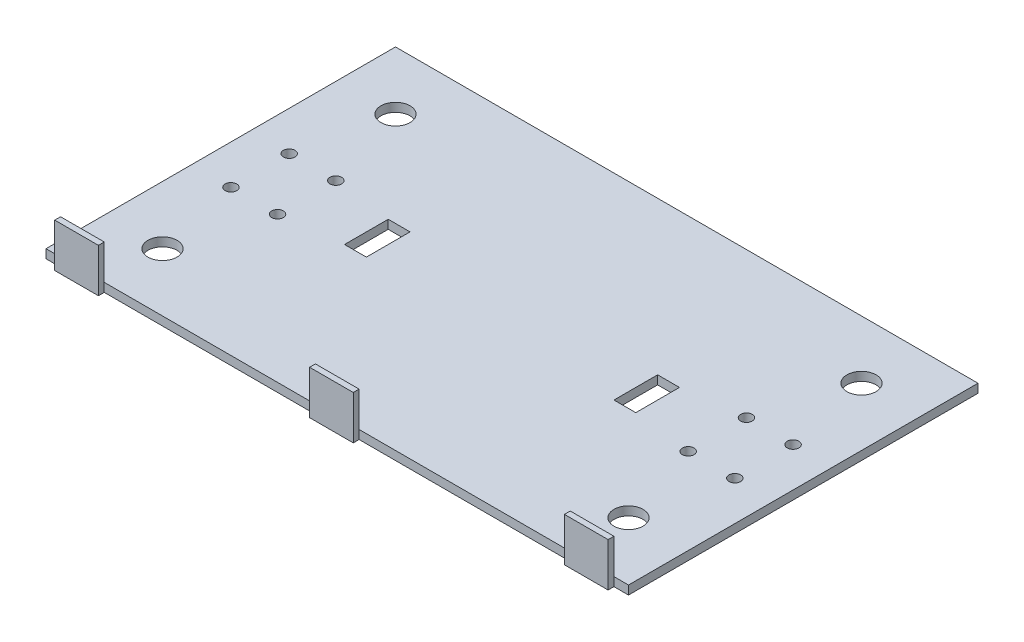
SolidWorks part; units mm, degrees
ref_plane "Front Plane" through (0, 0, 0) normal (0, 0, 1) x (1, 0, 0)
ref_plane "Top Plane" through (0, 0, 0) normal (0, 1, 0) x (1, 0, 0)
ref_plane "Right Plane" through (0, 0, 0) normal (1, 0, 0) x (0, 0, -1)
sketch "Sketch1" plane through (0, 0, 0) normal (0, 1, 0) x (1, 0, 0)
  line L1 (100, -60) -> (-100, -60)
  line L2 (100, -60) -> (100, 60)
  line L3 (100, 60) -> (-100, 60)
  line L4 (-100, -60) -> (-100, 60)
  line L5 (100, -60) -> (-100, 60) construction
  line L6 (100, 60) -> (-100, -60) construction
  point P0 (0, 0)
  dimension "D1" = 200
  dimension "D2" = 120
extrude "Boss-Extrude3" add sketch "Sketch1" along normal blind 1
sketch "Sketch3" plane through (0, 1, 0) normal (0, 1, 0) x (1, 0, 0)
  line L0 (-83.5355, 43.5355) -> (-76.4645, 36.4645) construction
  line L5 (-100, 60) -> (-100, -60) construction
  line L6 (-100, -60) -> (100, -60) construction
  line L7 (76.4645, 36.4645) -> (83.5355, 43.5355) construction
  line L11 (0, -55) -> (0, 55) construction
  line L15 (-55, 0) -> (55, 0) construction
  circle A0 centre (-80, 40) radius 5
  circle A2 centre (80, -40) radius 5
  circle A4 centre (80, 40) radius 5
  circle A5 centre (-80, -40) radius 5
  circle A7 centre (80, 40) radius 5
  circle A9 centre (80, -40) radius 5
  circle A11 centre (-80, -40) radius 5
  point P0 (0, 0)
  dimension "D3" = 10
  dimension "D4" = 10
  dimension "D5" = 10
  dimension "D6" = 10
  dimension "D1" = 20
  dimension "D2" = 20
extrude "Boss-Extrude4" add sketch "Sketch3" along normal blind 2
sketch "Sketch8" plane through (0, 3, 0) normal (0, 1, 0) x (1, 0, 0)
  line L0 (0, -1.65) -> (0, 1.65) construction
  line L1 (-1.65, 0) -> (1.65, 0) construction
  circle A1 centre (-80, 40) radius 5
  circle A3 centre (80, 40) radius 5
  circle A5 centre (80, -40) radius 5
  circle A6 centre (-80, -40) radius 5
  dimension "D2" = 10
sketch "Sketch10" plane through (0, 0, 60) normal (0, 0, 1) x (1, 0, 0)
  line L0 (-100, 0) -> (100, 0) construction
  line L5 (-95, 0) -> (-80, 0)
  line L6 (-95, 0) -> (-95, 15)
  line L7 (-95, 15) -> (-80, 15)
  line L8 (-80, 0) -> (-80, 15)
  line L9 (-100, 3) -> (-100, 0) construction
  line L10 (0, -0.55) -> (0, 0.55) construction
  line L11 (95, 0) -> (80, 0)
  line L12 (95, 0) -> (95, 15)
  line L13 (95, 15) -> (80, 15)
  line L14 (80, 0) -> (80, 15)
  line L16 (-7.5, 0) -> (7.5, 0)
  line L17 (-7.5, 0) -> (-7.5, 15)
  line L18 (-7.5, 15) -> (7.5, 15)
  line L19 (7.5, 0) -> (7.5, 15)
  point P18 (0, 0)
  point P19 (0, 0)
  point P21 (0, 0)
  point P22 (-15.244, -1.9886)
  dimension "D1" = 15
  dimension "D2" = 15
  dimension "D3" = 5
  dimension "D4" = 15
  dimension "D5" = 15
extrude "Boss-Extrude6" add sketch "Sketch10" along normal blind 2
sketch "Sketch12" plane through (0, 0, 0) normal (0, -1, 0) x (1, 0, 0)
  line L0 (-100, -60) -> (-100, 60) construction
  line L1 (1.65, 0) -> (-1.65, 0) construction
  line L2 (0, -1.65) -> (0, 1.65) construction
  line L3 (50, -7.5) -> (42.5, -7.5)
  line L8 (-50, 7.5) -> (-42.5, 7.5)
  line L9 (-50, 7.5) -> (-50, -7.5)
  line L10 (-50, -7.5) -> (-42.5, -7.5)
  line L11 (-42.5, 7.5) -> (-42.5, -7.5)
  line L12 (42.5, 7.5) -> (42.5, -7.5)
  line L13 (50, 7.5) -> (42.5, 7.5)
  line L14 (50, 7.5) -> (50, -7.5)
  circle A0 centre (-86.5, 10) radius 2
  circle A1 centre (-70.5, 10) radius 2
  circle A2 centre (-70.5, -10) radius 2
  circle A3 centre (-86.5, -10) radius 2
  circle A4 centre (86.5, -10) radius 2
  circle A5 centre (70.5, -10) radius 2
  circle A6 centre (70.5, 10) radius 2
  circle A7 centre (86.5, 10) radius 2
  point P6 (-100, 0)
  point P28 (-50, 0)
  dimension "D1" = 13.5
  dimension "D3" = 16
  dimension "D2" = 10
  dimension "D4" = 15
  dimension "D5" = 7.5
  dimension "D6" = 50
extrude "Cut-Extrude1" cut sketch "Sketch12" against normal through all
extrude "Cut-Extrude2" cut sketch "Sketch8" against normal blind 10
